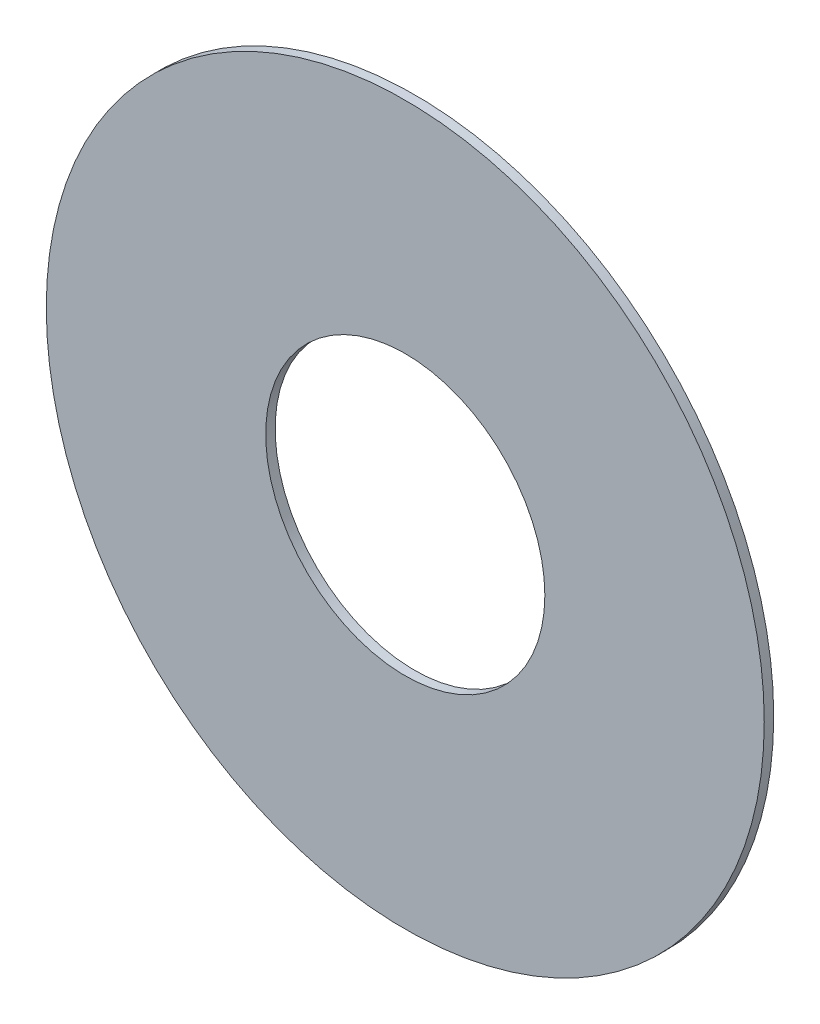
SolidWorks part; units mm, degrees
ref_plane "Спереди" through (0, 0, 0) normal (0, 0, 1) x (1, 0, 0)
ref_plane "Сверху" through (0, 0, 0) normal (0, 1, 0) x (1, 0, 0)
ref_plane "Справа" through (0, 0, 0) normal (1, 0, 0) x (0, 0, -1)
sketch "Эскиз1" plane through (0, 0, 0) normal (0, 0, 1) x (1, 0, 0)
  circle A0 centre (0, 0) radius 75.8769
  circle A1 centre (0, 0) radius 29.5
extrude "Printed_guard" add sketch "Эскиз1" along normal blind 2 from offset 42.5
